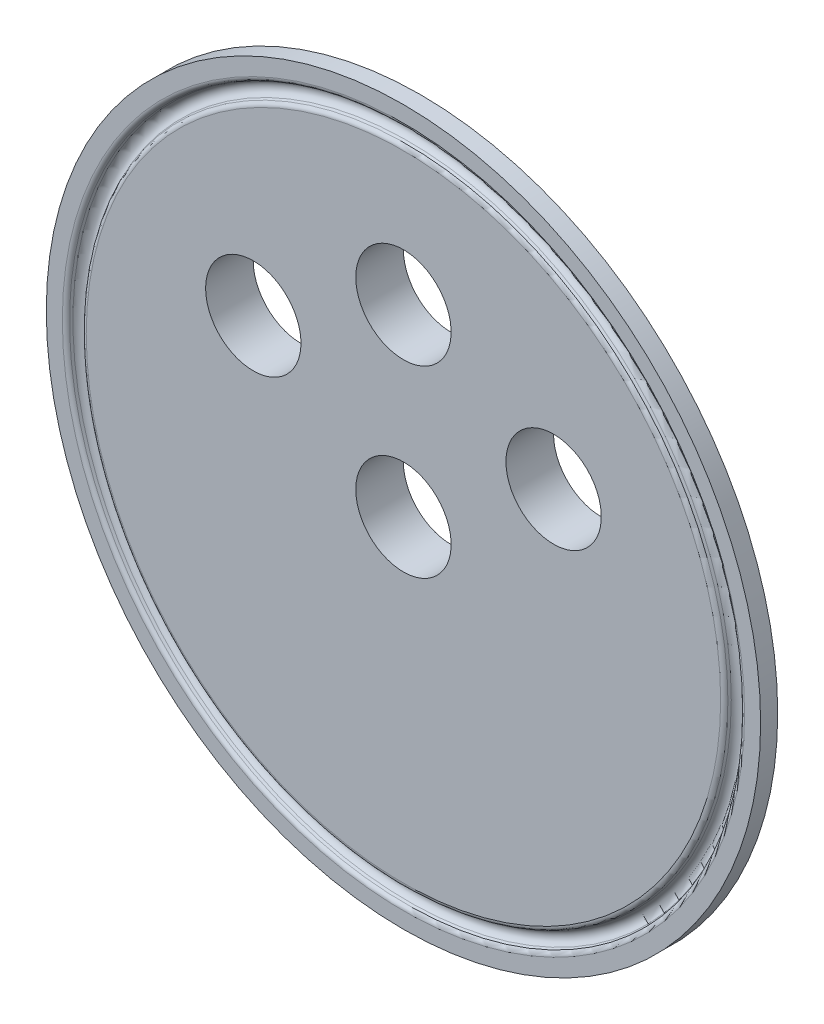
SolidWorks part; units mm, degrees
ref_plane "Front Plane" through (0, 0, 0) normal (0, 0, 1) x (1, 0, 0)
ref_plane "Top Plane" through (0, 0, 0) normal (0, 1, 0) x (1, 0, 0)
ref_plane "Right Plane" through (0, 0, 0) normal (1, 0, 0) x (0, 0, -1)
sketch "Sketch1" plane through (0, 0, 0) normal (1, 0, 0) x (0, 0, -1)
  line L0 (0, 0) -> (7.9248, 0) construction
  line L1 (0, 0) -> (0, 52.8099)
  line L2 (0, 59.4614) -> (2.8448, 59.4614)
  line L3 (2.8448, 59.4614) -> (7.9248, 45.5042)
  line L4 (7.9248, 45.5042) -> (7.9248, 0)
  line L5 (0, 56.7911) -> (0, 59.4614)
  line L6 (0.4797, 56.0663) -> (0.8729, 55.8994)
  line L7 (0.4797, 53.5347) -> (0.8729, 53.7016)
  line L8 (0, 56.2699) -> (0, 53.3311) construction
  line L9 (0, 54.8005) -> (0.4064, 54.8005) construction
  line L10 (0, 0) -> (7.9248, 0)
  arc A0 (0.8729, 53.7016) -> (0.8729, 55.8994) centre (0.4064, 54.8005) ccw
  arc A2 (0, 52.8099) -> (0.4797, 53.5347) centre (0.7874, 52.8099) cw
  arc A3 (0, 56.7911) -> (0.4797, 56.0663) centre (0.7874, 56.7911) ccw
  dimension "K" = 1.1938
  dimension "L" = 0.7874
  dimension "I" = 20
  dimension "C" = 91.0084
  dimension "F" = 2.8448
  dimension "H" = 0.4064
  dimension "B" = 109.601
  dimension "A" = 118.9228
  dimension "M" = 46
  dimension "N" = 23
  dimension "Length" = 7.9248
revolve "Revolve1" add sketch "Sketch1" angle 360 about L0
sketch "Sketch2" plane through (0, 0, -7.9248) normal (0, 0, -1) x (-1, 0, 0)
  circle A0 centre (-25, 16.5) radius 13.716 construction
  circle A1 centre (0, 30.6) radius 13.716 construction
  circle A2 centre (25, 16.5) radius 13.716 construction
  circle A3 centre (-25, 16.5) radius 7.9375
  circle A4 centre (0, 30.6) radius 7.9375
  circle A5 centre (25, 16.5) radius 7.9375
  circle A6 centre (0, 0) radius 7.9375
  circle A7 centre (0, 0) radius 13.716 construction
  dimension "D1" = 27.432
  dimension "D2" = 27.432
  dimension "D3" = 27.432
  dimension "D9" = 15.875
  dimension "D10" = 15.875
  dimension "D11" = 27.432
  dimension "D4" = 25
  dimension "D5" = 25
  dimension "D6" = 16.5
  dimension "D7" = 30.6
  dimension "D8" = 25
extrude "Cut-Extrude1" cut sketch "Sketch2" against normal through all
equation "\"D2@Sketch2\"=\"D1@Sketch2\""
equation "\"D3@Sketch2\"=\"D1@Sketch2\""
equation "\"D5@Sketch2\"=\"D4@Sketch2\""
equation "\"D8@Sketch2\"=\"D4@Sketch2\""
equation "\"D10@Sketch2\"=\"D9@Sketch2\""
equation "\"D11@Sketch2\"=\"D1@Sketch2\""
